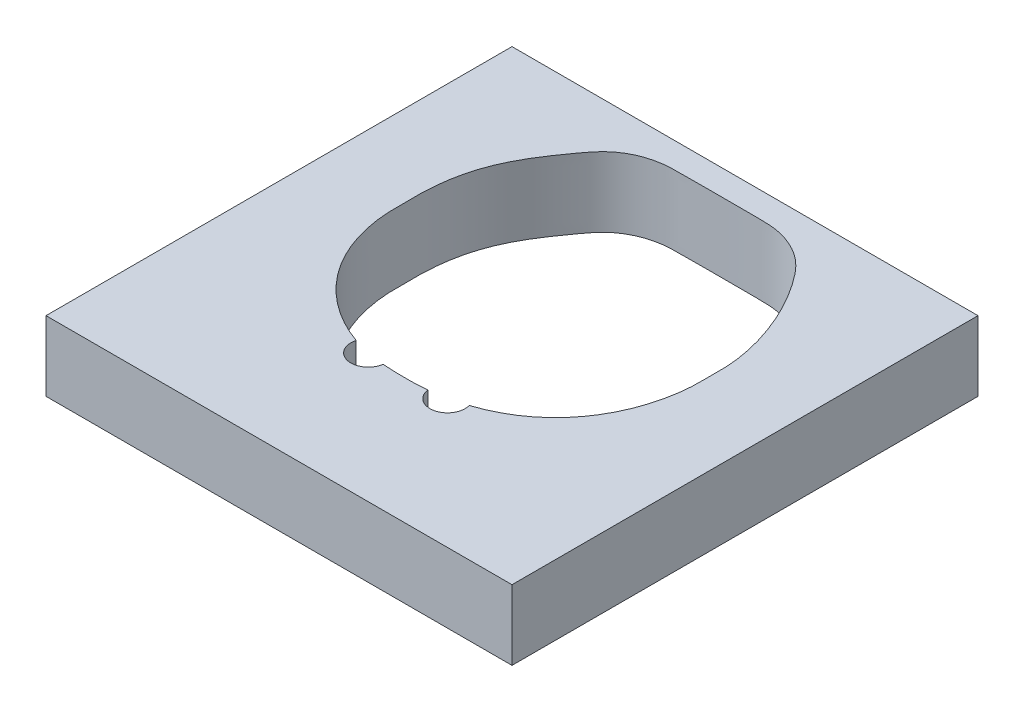
SolidWorks part; units mm, degrees
ref_plane "Plan de face" through (0, 0, 0) normal (0, 0, 1) x (1, 0, 0)
ref_plane "Plan de dessus" through (0, 0, 0) normal (0, 1, 0) x (1, 0, 0)
ref_plane "Plan de droite" through (0, 0, 0) normal (1, 0, 0) x (0, 0, -1)
ref_plane "Plan1" through (0, 0, 0) normal (0, 1, 0) x (1, 0, 0)
sketch "Esquisse1" plane through (0, 0, 0) normal (0, 1, 0) x (1, 0, 0)
  line L1 (-10, 8) -> (10, 8)
  line L2 (-10, 8) -> (-10, -12)
  line L3 (-10, -12) -> (10, -12)
  line L4 (10, 8) -> (10, -12)
  spline S0 degree 3 poles (-6.4938, -0.2013) (-6.572, 2.567) (-5.6328, 4.1026) (-3.9037, 6.4469) (-2.7582, 6.8993) (-0.8788, 6.9122) (1.1301, 6.9137) (2.7624, 6.8946) (3.9133, 6.3937) (5.6838, 4.1829) (6.5548, 1.8243) (6.4943, -0.0064) (6.5124, -0.675) (6.2456, -3.4367) (4.3253, -6.1825) (0.5423, -6.62) (-0.4249, -6.6075) (-3.0912, -6.4783) (-6.1228, -4.404) (-6.517, -0.7729) (-6.4938, -0.2013) (-6.572, 2.567) (-5.6328, 4.1026) knots -0.028087 -0.008777 -0.000975 0 0.112372 0.130276 0.173621 0.187169 0.252205 0.26694 0.319781 0.34342 0.479691 0.498677 0.514296 0.542967 0.756721 0.785787 0.80456 0.825241 0.971913 0.991223 0.999025 1 1.112372 1.130276 1.173621 only from (-6.5, 0.0214) to (-6.5, 0.0214)
  point P0 (-4.3092, 5.8708)
  point P1 (-2.0473, 6.9)
  point P3 (2.0473, 6.9)
  point P5 (4.3092, 5.8708)
  point P6 (11.1555, -10.0884)
  point P7 (-8.0374, 8.534)
  point P8 (8.1021, -7.8068)
  point P9 (6.5, 0.0214)
  point P11 (6.5, -0.6)
  point P13 (0.5, -6.6)
  point P15 (-0.5, -6.6)
  point P16 (-11.7283, -12.9067)
  point P17 (11.1884, 8.0244)
  point P19 (-6.5, -0.6)
  point P21 (-6.5, 0.0214)
  dimension "D1" = 20
  dimension "D2" = 20
  dimension "D3" = 10
  dimension "D4" = 12
extrude "Boss.-Extru.1" add sketch "Esquisse1" along normal blind 3
sketch "Esquisse3" plane through (0, 3, 0) normal (0, 1, 0) x (1, 0, 0)
  line L0 (0, 0) -> (0, -3.4245) construction
  circle A0 centre (-1.7, -6.4677) radius 0.75
  circle A2 centre (1.7, -6.4677) radius 0.75
  spline S1 degree 3 poles (-5.6328, 4.1026) (-6.572, 2.567) (-6.4938, -0.2013) (-6.517, -0.7729) (-6.1228, -4.404) (-3.0912, -6.4783) (-0.4249, -6.6075) (0.5423, -6.62) (4.3253, -6.1825) (6.2456, -3.4367) (6.5124, -0.675) (6.4943, -0.0064) (6.5548, 1.8243) (5.6838, 4.1829) (3.9133, 6.3937) (2.7624, 6.8946) (1.1301, 6.9137) (-0.8788, 6.9122) (-2.7582, 6.8993) (-3.9037, 6.4469) (-5.6328, 4.1026) (-6.572, 2.567) (-6.4938, -0.2013) knots -0.173621 -0.130276 -0.112372 0 0.000975 0.008777 0.028087 0.174759 0.19544 0.214213 0.243279 0.457033 0.485704 0.501323 0.520309 0.65658 0.680219 0.73306 0.747795 0.812831 0.826379 0.869724 0.887628 1 1.000975 1.008777 1.028087 only from (-6.5, 0.0214) to (-6.5, 0.0214) construction
  point P3 (0, 0)
  point P7 (0, 0)
  point P8 (-1.6, -6.4881)
  dimension "D2" = 1.5
  dimension "D1" = 1.7
extrude "Enlèv. mat.-Extru.1" cut sketch "Esquisse3" against normal blind 3
